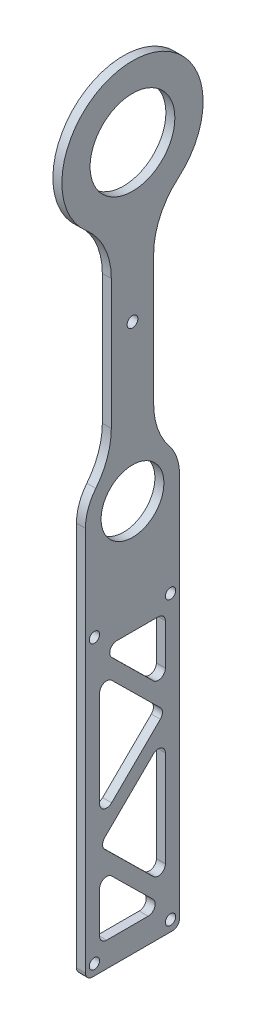
SolidWorks part; units mm, degrees
material "6061 Alloy"
ref_plane "Front Plane" through (0, 0, 0) normal (0, 0, 1) x (1, 0, 0)
ref_plane "Top Plane" through (0, 0, 0) normal (0, 1, 0) x (1, 0, 0)
ref_plane "Right Plane" through (0, 0, 0) normal (1, 0, 0) x (0, 0, -1)
sketch "Sketch1" plane through (0, 0, 0) normal (1, 0, 0) x (0, 0, -1)
  line L0 (-13.4747, 0) -> (13.4747, 0) construction
  line L1 (0, 0) -> (0, 35) construction
  line L2 (-13.4747, 0) -> (0, 35) construction
  line L3 (0, 35) -> (13.4747, 0) construction
  line L4 (13.4747, 0) -> (-13.4747, 0) construction
  line L5 (20.7574, -5) -> (-20.7574, -5)
  line L6 (-20.7574, -5) -> (-10.3702, 21.9802)
  line L7 (0, 48.9165) -> (1.1006, 46.0579) construction
  line L8 (0, 35) -> (0, 46.1125) construction
  line L9 (0, 35) -> (0, 46.1125) construction
  line L12 (-7.5, 35) -> (-7.5, 43.1999) construction
  line L13 (7.5, 35) -> (7.5, 43.1999) construction
  line L14 (-7.5, 35) -> (-7.5, 29.4356) construction
  line L15 (7.5, 35) -> (7.5, 29.4356) construction
  line L16 (-13.4747, 0) -> (13.4747, 0) construction
  line L17 (-13.4747, 0) -> (-13.4747, -100) construction
  line L18 (13.4747, 0) -> (13.4747, -100) construction
  line L19 (-13.4747, -100) -> (13.4747, -100) construction
  line L20 (-20.7574, -5) -> (20.7574, -5)
  line L21 (-20.7574, -5) -> (-20.7574, -103.81)
  line L22 (20.7574, -5) -> (20.7574, -103.81)
  line L23 (-20.7574, -103.81) -> (20.7574, -103.81)
  line L24 (-10.3702, 21.9802) -> (-8.2317, 27.535) construction
  line L25 (-7.5, 29.4356) -> (-6.6746, 31.5795) construction
  line L26 (-20.7574, -5) -> (0, 48.9165) construction
  line L27 (8.2317, 27.535) -> (10.3702, 21.9802) construction
  line L28 (10.3702, 21.9802) -> (20.7574, -5)
  line L29 (0, 48.9165) -> (20.7574, -5) construction
  line L30 (-7.5, 43.1999) -> (-7.5, 49.8595) construction
  line L31 (-7.5, 49.8595) -> (-7.5, 145)
  line L32 (7.5, 43.1999) -> (7.5, 49.8595) construction
  line L33 (7.5, 49.8595) -> (7.5, 145)
  line L34 (-8.2317, 27.535) -> (-7.5, 29.4356) construction
  line L35 (-6.6746, 31.5795) -> (-1.1006, 46.0579) construction
  line L36 (-1.1006, 46.0579) -> (0, 48.9165) construction
  line L37 (1.1006, 46.0579) -> (6.6746, 31.5795) construction
  line L38 (6.6746, 31.5795) -> (7.5, 29.4356) construction
  line L39 (7.5, 29.4356) -> (8.2317, 27.535) construction
  line L40 (0, 46.1125) -> (0, 48.9165) construction
  line L41 (0, 48.9165) -> (0, 145) construction
  line L42 (0, 46.1125) -> (0, 48.9165) construction
  line L43 (0, 48.9165) -> (0, 145) construction
  line L44 (-16.645, 35) -> (-16.645, 5.6818)
  line L45 (16.645, 35) -> (16.645, 5.6818)
  circle A0 centre (-13.4747, 0) radius 1.8288
  circle A1 centre (0, 35) radius 11.1125
  circle A2 centre (13.4747, 0) radius 1.8288
  circle A3 centre (0, 145) radius 3 construction
  arc A6 (-7.5, 35) -> (-6.6746, 31.5795) centre (0, 35) ccw construction
  arc A7 (7.5, 145) -> (-7.5, 145) centre (0, 145) ccw
  circle A8 centre (-13.4747, -100) radius 1.8288
  circle A9 centre (13.4747, -100) radius 1.8288
  circle A17 centre (0, 145) radius 15
  circle A18 centre (0, 145) radius 25
  arc A19 (10.3702, 21.9802) -> (7.5, 49.8595) centre (0, 35) ccw
  arc A20 (-10.3702, 21.9802) -> (-5.9803, 19.4664) centre (0, 35) ccw construction
  circle A21 centre (0, 35) radius 16.645 construction
  arc A22 (-5.9803, 19.4664) -> (0, 18.355) centre (0, 35) ccw construction
  arc A23 (0, 18.355) -> (5.9803, 19.4664) centre (0, 35) ccw construction
  arc A24 (5.9803, 19.4664) -> (10.3702, 21.9802) centre (0, 35) ccw construction
  arc A25 (0, 51.645) -> (-7.5, 49.8595) centre (0, 35) ccw construction
  arc A26 (-7.5, 49.8595) -> (-10.3702, 21.9802) centre (0, 35) ccw
  arc A27 (7.5, 49.8595) -> (0, 51.645) centre (0, 35) ccw construction
  arc A28 (6.6746, 31.5795) -> (7.5, 35) centre (0, 35) ccw construction
  arc A29 (2.6946, 28.0008) -> (6.6746, 31.5795) centre (0, 35) ccw construction
  arc A30 (0, 27.5) -> (2.6946, 28.0008) centre (0, 35) ccw construction
  arc A31 (-2.6946, 28.0008) -> (0, 27.5) centre (0, 35) ccw construction
  arc A32 (-6.6746, 31.5795) -> (-2.6946, 28.0008) centre (0, 35) ccw construction
  point P4 (0, 0)
  point P14 (0, 90)
  point P34 (0, 145)
  dimension "D3" = 3.6576
  dimension "D4" = 22.225
  dimension "D7" = 6
  dimension "D11" = 16.645
  dimension "D13" = 30
  dimension "D14" = 50
  dimension "D1" = 26.9494
  dimension "D5" = 110
  dimension "D6" = 15
  dimension "D8" = 100
  dimension "D9" = 3.81
  dimension "D10" = 35
  dimension "D2" = 5
extrude "Boss-Extrude1" add sketch "Sketch1" along normal blind 3.175 contours A6 L7 L15 | L21 L23 L22 L5 A9 A8 | L31 A26 L6 L5 L28 A19 L33 A18 A0 A1 A2 | A19 L28 L45 | A26 L44 L6 | L31 A18 L33 A17 | L33 A18 L31 A17
sketch "Sketch2" plane through (3.175, 0, 0) normal (1, 0, 0) x (0, 0, -1)
  line L0 (-11.645, -5) -> (11.645, -5) construction
  line L1 (-11.645, -95) -> (11.645, -95) construction
  line L2 (11.645, -95) -> (11.645, -5) construction
  line L3 (-11.645, -95) -> (-11.645, -5) construction
  line L6 (11.645, -38.5118) -> (-11.645, -61.4882) construction
  line L7 (11.645, -5) -> (-11.645, -5)
  line L8 (-11.645, -5) -> (11.645, -27.9764)
  line L9 (11.645, -27.9764) -> (11.645, -5)
  line L10 (-11.645, -12.0236) -> (11.645, -35)
  line L11 (11.645, -35) -> (-11.645, -57.9764)
  line L12 (-11.645, -57.9764) -> (-11.645, -35)
  line L13 (-11.645, -35) -> (-11.645, -12.0236)
  line L14 (-11.645, -72.0236) -> (-11.645, -95)
  line L15 (-11.645, -95) -> (11.645, -95)
  line L16 (11.645, -95) -> (-11.645, -72.0236)
  line L17 (11.645, -42.0236) -> (11.645, -65)
  line L18 (11.645, -65) -> (11.645, -87.9764)
  line L19 (11.645, -87.9764) -> (-11.645, -65)
  line L20 (-11.645, -65) -> (11.645, -42.0236)
  line L21 (16.645, -1056.0877) -> (16.645, 48943.9123) construction
  line L22 (-16.645, -1060.2922) -> (-16.645, 48939.7078) construction
  line L23 (16.645, 23.8875) -> (-16.645, 23.8875) construction
  line L24 (-20.7574, -103.81) -> (-16.645, -103.81)
  line L25 (-20.7574, -103.81) -> (-20.7574, 23.8875)
  line L26 (-16.645, -103.81) -> (-16.645, 23.8875)
  line L27 (-20.7574, 23.8875) -> (-16.645, 23.8875)
  line L28 (-20.7574, -103.81) -> (20.7574, -103.81) construction
  line L29 (20.7574, -103.81) -> (16.645, -103.81)
  line L30 (20.7574, -103.81) -> (20.7574, 23.8875)
  line L31 (16.645, -103.81) -> (16.645, 23.8875)
  line L32 (20.7574, 23.8875) -> (16.645, 23.8875)
  circle A0 centre (13.4747, 0) radius 1.8288 construction
  circle A1 centre (13.4747, -100) radius 1.8288 construction
  circle A2 centre (0, 35) radius 11.1125 construction
  point P6 (11.645, -50)
  point P10 (0, 23.8875)
  point P21 (0, -50)
  dimension "D1" = 33.29
  dimension "D2" = 5
  dimension "D3" = 5
  dimension "D4" = 5
  dimension "D5" = 5
  dimension "D6" = 2.5
  dimension "D8" = 5
  dimension "D7" = 2
extrude "Cut-Extrude1" cut sketch "Sketch2" against normal up to next
fillet "Fillet3" radius 2.5 14 edges at (1.5875, -57.9764, 11.645) (1.5875, -35, -11.645) (1.5875, -95, -11.645) (1.5875, -72.0236, 11.645) (1.5875, -95, 11.645) (1.5875, -27.9764, -11.645) (1.5875, -5, -11.645) (1.5875, -12.0236, 11.645) (1.5875, -5, 11.645) (1.5875, -87.9764, -11.645) (1.5875, -42.0236, -11.645) (1.5875, -65, 11.645) (1.5875, -103.81, -16.645) (1.5875, -103.81, 16.645)
fillet "Fillet4" radius 25 4 edges at (1.5875, 121.1515, 7.5) (1.5875, 121.1515, -7.5) (1.5875, 49.8595, -7.5) (1.5875, 49.8595, 7.5)
hole_wizard "#6 Clearance Hole1" positions "Sketch3" profile "Sketch4" hole size "#6" standard "ANSI Inch" end condition up to next
sketch "Sketch3" plane through (3.175, 0, 0) normal (1, 0, 0) x (0, 0, -1)
  circle A0 centre (0, 35) radius 11.1125 construction
  point P0 (0, 90)
  dimension "D1" = 55
sketch "Sketch4" plane through (3.175, 90, 0) normal (0, 1, 0) x (0, 0, -1)
  line L0 (0, 0) -> (0, 3.175)
  line L1 (0, 3.175) -> (1.8986, 3.175)
  line L2 (1.8986, 3.175) -> (1.8986, 0)
  line L5 (1.8986, 0) -> (0, 0)
  line L11 (0, -6.35) -> (0, 107.95) construction
  dimension "Thru Hole Dia." = 3.7973
  dimension "Thru Hole Depth" = 3.175
